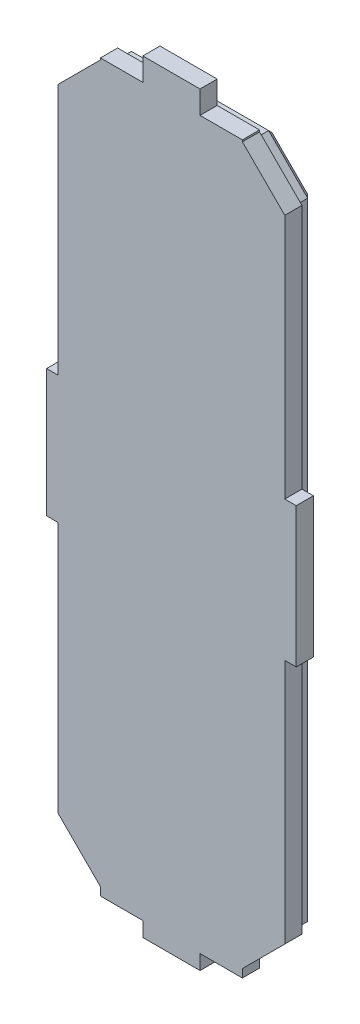
SolidWorks part; units mm, degrees
ref_plane "Front Plane" through (0, 0, 0) normal (0, 0, 1) x (1, 0, 0)
ref_plane "Top Plane" through (0, 0, 0) normal (0, 1, 0) x (1, 0, 0)
ref_plane "Right Plane" through (0, 0, 0) normal (1, 0, 0) x (0, 0, -1)
sketch "Sketch1" plane through (0, 0, 0) normal (0, 0, 1) x (1, 0, 0)
  line L16 (-135.195, -141.3179) -> (-131.7829, -144.73)
  line L17 (-131.7829, -144.73) -> (-119.7971, -144.73)
  line L18 (-119.7971, -144.73) -> (-116.385, -141.3179)
  line L19 (-116.385, -141.3179) -> (-116.385, -86.5863)
  line L20 (-116.385, -86.5863) -> (-119.7971, -83.1741)
  line L21 (-135.195, -86.5863) -> (-135.195, -141.3179)
  line L22 (-131.7829, -83.1741) -> (-135.195, -86.5863)
  line L23 (-119.7971, -83.1741) -> (-131.7829, -83.1741)
  line L24 (-135.195, -141.3179) -> (-131.7829, -144.73)
  line L25 (-131.7829, -144.73) -> (-119.7971, -144.73)
  line L26 (-119.7971, -144.73) -> (-116.385, -141.3179)
  line L27 (-116.385, -141.3179) -> (-116.385, -86.5863)
  line L28 (-116.385, -86.5863) -> (-119.7971, -83.1741)
  line L29 (-135.195, -86.5863) -> (-135.195, -141.3179)
  line L30 (-131.7829, -83.1741) -> (-135.195, -86.5863)
  line L31 (-119.7971, -83.1741) -> (-131.7829, -83.1741)
  dimension "D1" = 0.15
extrude "Boss-Extrude1" add sketch "Sketch1" against normal blind 1.5
sketch "Sketch2" plane through (0, 0, 0) normal (0, 0, 1) x (1, 0, 0)
  line L16 (-135.695, -86.3791) -> (-135.695, -141.525)
  line L17 (-135.695, -141.525) -> (-131.99, -145.23)
  line L18 (-131.99, -145.23) -> (-119.59, -145.23)
  line L19 (-119.59, -145.23) -> (-115.885, -141.525)
  line L20 (-115.885, -141.525) -> (-115.885, -86.3791)
  line L21 (-115.885, -86.3791) -> (-119.59, -82.6741)
  line L22 (-119.59, -82.6741) -> (-131.99, -82.6741)
  line L23 (-131.99, -82.6741) -> (-135.695, -86.3791)
  line L24 (-135.695, -86.3791) -> (-135.695, -141.525)
  line L25 (-135.695, -141.525) -> (-131.99, -145.23)
  line L26 (-131.99, -145.23) -> (-119.59, -145.23)
  line L27 (-119.59, -145.23) -> (-115.885, -141.525)
  line L28 (-115.885, -141.525) -> (-115.885, -86.3791)
  line L29 (-115.885, -86.3791) -> (-119.59, -82.6741)
  line L30 (-119.59, -82.6741) -> (-131.99, -82.6741)
  line L31 (-131.99, -82.6741) -> (-135.695, -86.3791)
  dimension "D1" = 0.5
extrude "Boss-Extrude2" add sketch "Sketch2" along normal blind 1.5
sketch "Sketch3" plane through (0, 0, 1.5) normal (0, 0, 1) x (1, 0, 0)
  line L0 (-131.845, -83.0241) -> (-119.735, -83.0241) construction
  line L1 (-131.99, -83.526) -> (-128.29, -83.526)
  line L2 (-131.99, -83.526) -> (-131.99, -82.5222)
  line L3 (-131.99, -82.5222) -> (-128.29, -82.5222)
  line L4 (-119.59, -83.526) -> (-119.59, -82.5222)
  line L7 (-119.735, -144.88) -> (-131.845, -144.88) construction
  line L8 (-131.99, -143.8169) -> (-128.29, -143.8169)
  line L9 (-131.99, -143.8169) -> (-131.99, -145.9431)
  line L10 (-131.99, -145.9431) -> (-128.29, -145.9431)
  line L11 (-119.59, -143.8169) -> (-119.59, -145.9431)
  line L12 (-123.29, -82.5222) -> (-119.59, -82.5222)
  line L13 (-128.29, -82.5222) -> (-128.29, -80.5222)
  line L14 (-115.885, -141.525) -> (-115.885, -86.3791) construction
  line L15 (-116.885, -107.8507) -> (-114.885, -107.8507)
  line L16 (-116.885, -107.8507) -> (-116.885, -120.0534)
  line L17 (-116.885, -120.0534) -> (-114.885, -120.0534)
  line L18 (-114.885, -107.8507) -> (-114.885, -120.0534)
  line L19 (-116.885, -107.8507) -> (-114.885, -120.0534) construction
  line L20 (-116.885, -120.0534) -> (-114.885, -107.8507) construction
  line L21 (-135.695, -86.3791) -> (-135.695, -141.525) construction
  line L22 (-136.695, -108.3783) -> (-134.695, -108.3783)
  line L23 (-136.695, -108.3783) -> (-136.695, -119.5258)
  line L24 (-136.695, -119.5258) -> (-134.695, -119.5258)
  line L25 (-134.695, -108.3783) -> (-134.695, -119.5258)
  line L26 (-136.695, -108.3783) -> (-134.695, -119.5258) construction
  line L27 (-136.695, -119.5258) -> (-134.695, -108.3783) construction
  line L28 (-131.99, -145.23) -> (-119.59, -145.23) construction
  line L29 (-128.29, -84.5222) -> (-123.29, -84.5222)
  line L30 (-128.29, -84.5222) -> (-128.29, -83.526)
  line L31 (-128.29, -80.5222) -> (-123.29, -80.5222)
  line L32 (-123.29, -84.5222) -> (-123.29, -83.526)
  line L35 (-128.29, -143.23) -> (-123.29, -143.23)
  line L36 (-128.29, -143.23) -> (-128.29, -143.8169)
  line L37 (-128.29, -147.23) -> (-123.29, -147.23)
  line L38 (-123.29, -143.23) -> (-123.29, -143.8169)
  line L41 (-128.29, -145.9431) -> (-128.29, -147.23)
  line L46 (-123.29, -145.9431) -> (-123.29, -147.23)
  line L47 (-123.29, -145.9431) -> (-119.59, -145.9431)
  line L49 (-123.29, -143.8169) -> (-119.59, -143.8169)
  line L53 (-123.29, -83.526) -> (-119.59, -83.526)
  line L56 (-123.29, -82.5222) -> (-123.29, -80.5222)
  point P0 (-125.79, -83.0241)
  point P7 (-125.79, -144.88)
  point P15 (-115.885, -113.9521)
  point P22 (-135.695, -113.9521)
  point P29 (-125.79, -82.5222)
  point P34 (-125.79, -145.23)
  dimension "D1" = 1
  dimension "D2" = 2
  dimension "D3" = 5
extrude "Boss-Extrude3" add sketch "Sketch3" against normal up to surface (1.5 mm away) up to face at (-125.79, -113.9521, 0)
chamfer "Chamfer2" distance 0.5 angle 45 8 edges at (-133.4889, -143.0239, -1.5) (-125.79, -144.73, -1.5) (-118.0911, -143.0239, -1.5) (-116.385, -113.9521, -1.5) (-118.0911, -84.8802, -1.5) (-125.79, -83.1741, -1.5) (-133.4889, -84.8802, -1.5) (-135.195, -113.9521, -1.5)
